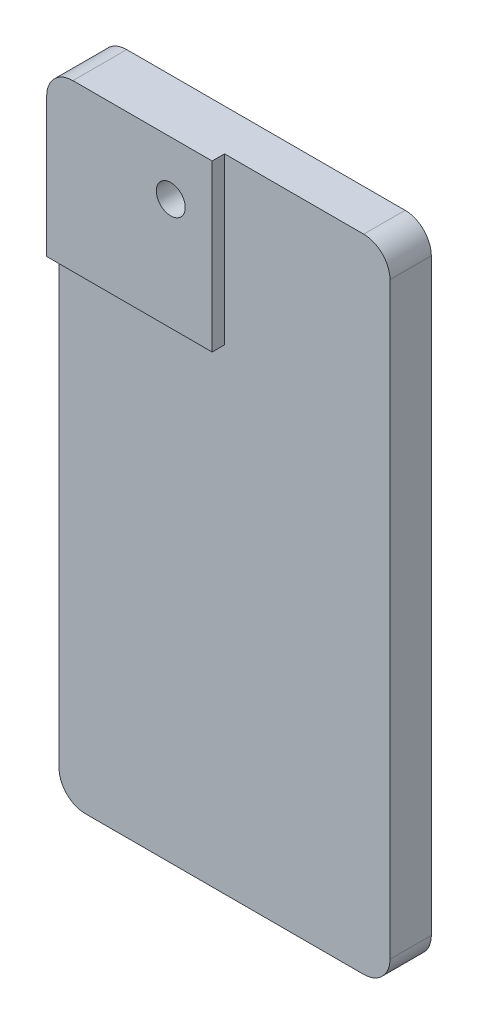
SolidWorks part; units mm, degrees
ref_plane "Front Plane" through (0, 0, 0) normal (0, 0, 1) x (1, 0, 0)
ref_plane "Top Plane" through (0, 0, 0) normal (0, 1, 0) x (1, 0, 0)
ref_plane "Right Plane" through (0, 0, 0) normal (1, 0, 0) x (0, 0, -1)
sketch "Sketch1" plane through (0, 0, 0) normal (0, 0, 1) x (1, 0, 0)
  line L1 (-40, 77.5) -> (40, 77.5)
  line L2 (-40, 77.5) -> (-40, -77.5)
  line L3 (-40, -77.5) -> (40, -77.5)
  line L4 (40, 77.5) -> (40, -77.5)
  line L5 (-40, 77.5) -> (40, -77.5) construction
  line L6 (-40, -77.5) -> (40, 77.5) construction
  point P0 (0, 0)
  dimension "D1" = 80
  dimension "D2" = 155
extrude "Boss-Extrude1" add sketch "Sketch1" along normal mid plane 10
sketch "Sketch2" plane through (0, 0, 5) normal (0, 0, 1) x (1, 0, 0)
  line L1 (-40, 77.5) -> (0, 77.5)
  line L2 (-40, 77.5) -> (-40, 37.5)
  line L3 (-40, 37.5) -> (0, 37.5)
  line L4 (0, 77.5) -> (0, 37.5)
  dimension "D1" = 40
  dimension "D2" = 40
extrude "Boss-Extrude2" add sketch "Sketch2" along normal blind 3
sketch "Sketch3" plane through (0, 0, 8) normal (0, 0, 1) x (1, 0, 0)
  line L0 (-40, 77.5) -> (-40, 37.5) construction
  line L1 (0, 77.5) -> (-40, 77.5) construction
  circle A0 centre (-10, 64.5) radius 3.5
  dimension "D3" = 7
  dimension "D1" = 30
  dimension "D2" = 13
extrude "Cut-Extrude1" cut sketch "Sketch3" against normal through all
fillet "Fillet1" radius 6.35 4 edges at (40, -77.5, 0) (-40, -77.5, 0) (40, 77.5, 0) (-40, 77.5, 1.5)
